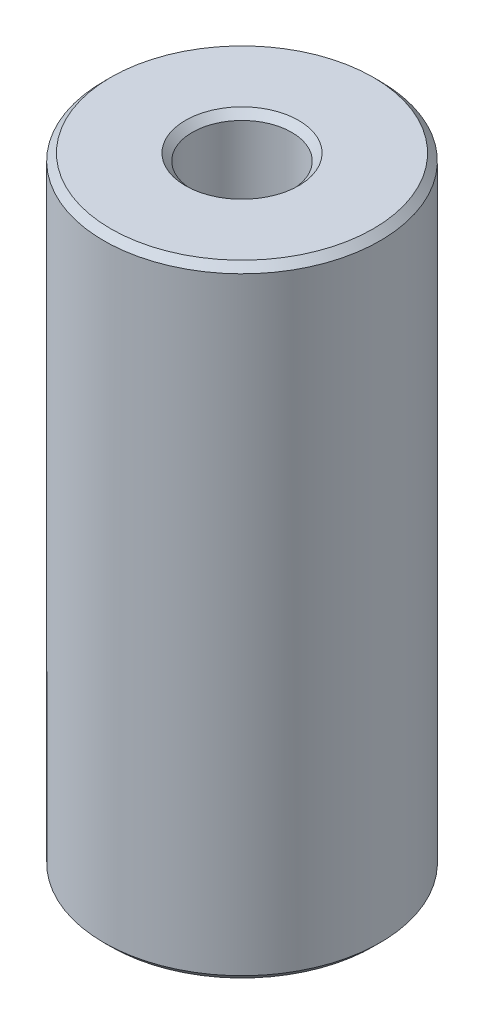
SolidWorks part; units mm, degrees
material "1060 slitina"
ref_plane "Přední rovina" through (0, 0, 0) normal (0, 0, 1) x (1, 0, 0)
ref_plane "Horní rovina" through (0, 0, 0) normal (0, 1, 0) x (1, 0, 0)
ref_plane "Pravá rovina" through (0, 0, 0) normal (1, 0, 0) x (0, 0, -1)
sketch "Skica2" plane through (0, 0, 0) normal (0, 1, 0) x (1, 0, 0)
  circle A0 centre (0, 0) radius 10
  circle A1 centre (0, 0) radius 3.6
  dimension "D1" = 20
  dimension "D2" = 7.2
extrude "Přidat vysunutím1" add sketch "Skica2" along normal blind 45
chamfer "Zkosení1" distance 0.5 angle 45 4 edges at (0, 0, 3.6) (0, 45, 3.6) (0, 45, 10) (0, 0, 10)
